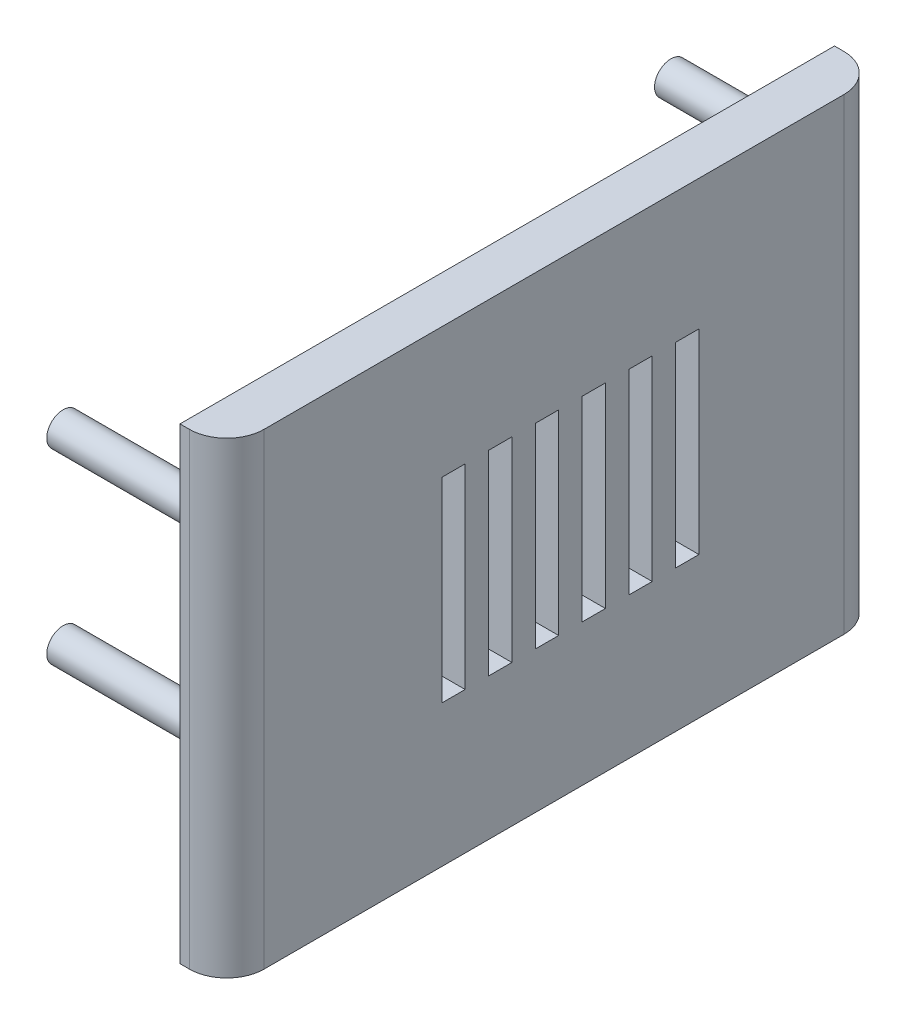
SolidWorks part; units mm, degrees
ref_plane "Front Plane" through (0, 0, 0) normal (0, 0, 1) x (1, 0, 0)
ref_plane "Top Plane" through (0, 0, 0) normal (0, 1, 0) x (1, 0, 0)
ref_plane "Right Plane" through (0, 0, 0) normal (1, 0, 0) x (0, 0, -1)
sketch "Sketch2" plane through (0, 0, 0) normal (1, 0, 0) x (0, 0, -1)
  line L1 (70, -50) -> (-70, -50)
  line L2 (70, -50) -> (70, 50)
  line L3 (70, 50) -> (-70, 50)
  line L4 (-70, -50) -> (-70, 50)
  line L5 (70, -50) -> (-70, 50) construction
  line L6 (70, 50) -> (-70, -50) construction
  point P0 (0, 0)
  dimension "D1" = 100
  dimension "D2" = 140
extrude "Boss-Extrude1" add sketch "Sketch2" along normal blind 10
sketch "Sketch3" plane through (0, 0, 0) normal (-1, 0, 0) x (0, 0, 1)
  line L2 (70, -50) -> (-70, -50) construction
  line L4 (-70, -50) -> (-70, 50) construction
  line L6 (70, 50) -> (70, -50) construction
  circle A0 centre (-65, 31.6267) radius 3.5
  circle A1 centre (-65, -8.3733) radius 3.5
  circle A2 centre (65, 31.6267) radius 3.5
  circle A3 centre (65, -8.3733) radius 3.5
  point P8 (0, 0)
  point P9 (0, 0)
  point P10 (0, 0)
  point P11 (0, 0)
  point P12 (0, 0)
  point P13 (-63.5613, 34.2916)
  dimension "D3" = 7
  dimension "D1" = 5
  dimension "D2" = 40
  dimension "D4" = 41.6267
  dimension "D5" = 5
extrude "Boss-Extrude2" add sketch "Sketch3" along normal blind 30
fillet "Fillet1" radius 8 2 edges at (10, 0, -70) (10, 0, 70)
sketch "Sketch4" plane through (10, 0, 0) normal (1, 0, 0) x (0, 0, -1)
  line L0 (16, 22.1) -> (21, 22.1)
  line L1 (26, 22.1) -> (31, 22.1)
  line L2 (26, 22.1) -> (26, -19.7)
  line L3 (26, -19.7) -> (31, -19.7)
  line L4 (31, 22.1) -> (31, -19.7)
  line L5 (16, 22.1) -> (16, -19.7)
  line L6 (16, -19.7) -> (21, -19.7)
  line L7 (21, 22.1) -> (21, -19.7)
  line L8 (-4, 22.1) -> (1, 22.1)
  line L9 (-4, 22.1) -> (-4, -19.7)
  line L10 (-4, -19.7) -> (1, -19.7)
  line L11 (1, 22.1) -> (1, -19.7)
  line L12 (6, 22.1) -> (11, 22.1)
  line L13 (6, 22.1) -> (6, -19.7)
  line L14 (6, -19.7) -> (11, -19.7)
  line L15 (11, 22.1) -> (11, -19.7)
  line L16 (-24, 22.1) -> (-19, 22.1)
  line L17 (-24, 22.1) -> (-24, -19.7)
  line L18 (-24, -19.7) -> (-19, -19.7)
  line L19 (-19, 22.1) -> (-19, -19.7)
  line L20 (-14, 22.1) -> (-9, 22.1)
  line L21 (-14, 22.1) -> (-14, -19.7)
  line L22 (-14, -19.7) -> (-9, -19.7)
  line L23 (-9, 22.1) -> (-9, -19.7)
  line L24 (62, -50) -> (62, 50) construction
  line L26 (62, 50) -> (-62, 50) construction
  point P24 (0, 0)
  point P25 (0, 0)
  point P26 (0, 0)
  dimension "D1" = 5
  dimension "D2" = 5
  dimension "D3" = 5
  dimension "D4" = 5
  dimension "D5" = 5
  dimension "D6" = 5
  dimension "D7" = 31
  dimension "D8" = 27.9
  dimension "D9" = 41.8
extrude "Cut-Extrude1" cut sketch "Sketch4" against normal blind 30
